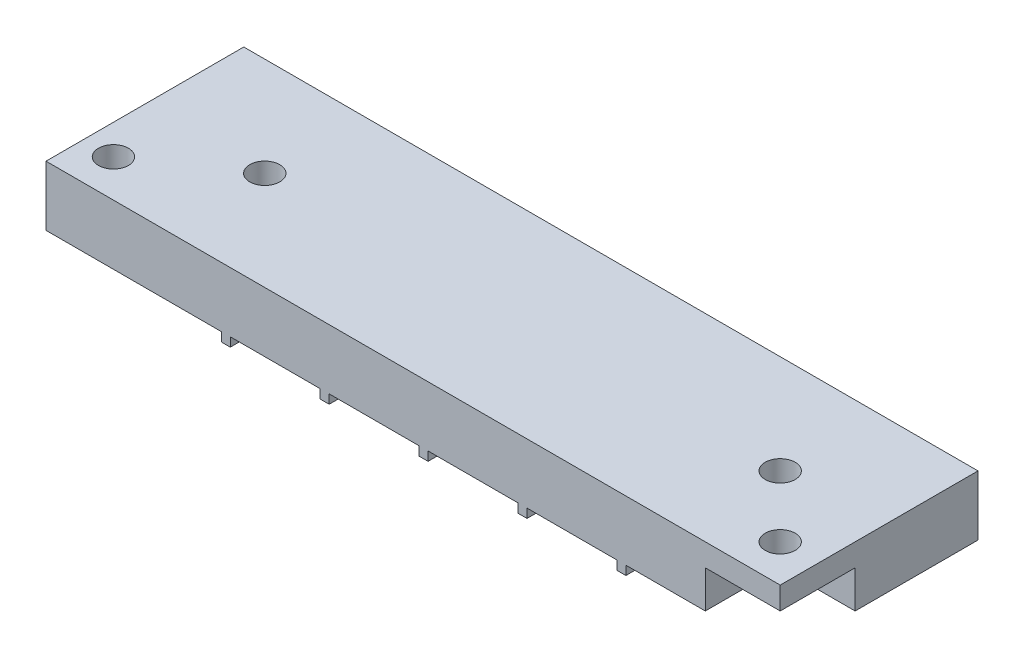
SolidWorks part; units mm, degrees
ref_plane "정면" through (0, 0, 0) normal (0, 0, 1) x (1, 0, 0)
ref_plane "윗면" through (0, 0, 0) normal (0, 1, 0) x (1, 0, 0)
ref_plane "우측면" through (0, 0, 0) normal (1, 0, 0) x (0, 0, -1)
sketch "스케치1" plane through (0, 0, 0) normal (0, 0, 1) x (1, 0, 0)
  line L0 (0, 8.45) -> (110, 8.45)
  line L1 (110, 8.45) -> (110, -8.45)
  line L2 (110, -8.45) -> (0, -8.45)
  line L4 (110, 8.45) -> (30, 8.45) construction
  line L5 (110, 8.45) -> (110, -8.45) construction
  line L6 (110, -8.45) -> (30, -8.45) construction
  line L7 (30, 8.45) -> (30, -8.45) construction
  arc A0 (0, 8.45) -> (0, -8.45) centre (0, 0) ccw
  circle A1 centre (0, 0) radius 5.95 construction
  circle A2 centre (-5.95, 0) radius 1.25
  circle A3 centre (0, 5.95) radius 1.25
  circle A4 centre (5.95, 0) radius 1.25
  circle A5 centre (0, -5.95) radius 1.25
  dimension "D1" = 16.9
  dimension "D4" = 2.5
  dimension "D5" = 2.5
  dimension "D2" = 80
  dimension "D3" = 30
extrude "보스-돌출1" add sketch "스케치1" along normal blind 2.5
sketch "스케치2" plane through (0, 0, 0) normal (0, 0, -1) x (-1, 0, 0)
  line L2 (-110, -8.45) -> (-28, -8.45)
  line L3 (-110, -8.45) -> (-110, -1.45)
  line L4 (-110, -1.45) -> (-28, -1.45)
  line L7 (-28, -8.45) -> (-28, -1.45)
  dimension "D1" = 7
  dimension "D2" = 82
extrude "컷-돌출1" cut sketch "스케치2" against normal blind 2.5
sketch "스케치3" plane through (0, 0, 0) normal (0, 0, -1) x (-1, 0, 0)
  line L1 (-107, 2.55) -> (-28, 2.55)
  line L2 (-107, 2.55) -> (-107, -1.45)
  line L3 (-107, -1.45) -> (-28, -1.45)
  line L4 (-28, 2.55) -> (-28, -1.45)
  dimension "D1" = 4
extrude "보스-돌출2" add sketch "스케치3" along normal blind 10.7
sketch "스케치4" plane through (0, -1.45, 0) normal (0, -1, 0) x (1, 0, 0)
  line L0 (28, -10.7) -> (107, -10.7) construction
  line L1 (67.5, -10.7) -> (67.5, 2.5) construction
  line L2 (28, 2.5) -> (110, 2.5) construction
  line L3 (73.8, -10.7) -> (74.4, -10.7)
  line L4 (67.2, -10.7) -> (67.8, -10.7)
  line L5 (67.2, -10.7) -> (67.2, 2.5)
  line L6 (67.2, 2.5) -> (67.8, 2.5)
  line L7 (67.8, -10.7) -> (67.8, 2.5)
  line L8 (67.2, -10.7) -> (67.8, 2.5) construction
  line L9 (67.2, 2.5) -> (67.8, -10.7) construction
  line L10 (73.8, -10.7) -> (73.8, 2.5)
  line L11 (73.8, 2.5) -> (74.4, 2.5)
  line L12 (74.4, -10.7) -> (74.4, 2.5)
  line L13 (34.6, -10.7) -> (113.6, -10.7) construction
  line L14 (74.1, -10.7) -> (74.1, 2.5) construction
  line L15 (73.8, -10.7) -> (74.4, 2.5) construction
  line L16 (73.8, 2.5) -> (74.4, -10.7) construction
  line L17 (80.4, -10.7) -> (81, -10.7)
  line L18 (80.4, -10.7) -> (80.4, 2.5)
  line L19 (80.4, 2.5) -> (81, 2.5)
  line L20 (81, -10.7) -> (81, 2.5)
  line L21 (41.2, -10.7) -> (120.2, -10.7) construction
  line L22 (80.7, -10.7) -> (80.7, 2.5) construction
  line L23 (80.4, -10.7) -> (81, 2.5) construction
  line L24 (80.4, 2.5) -> (81, -10.7) construction
  line L25 (87, -10.7) -> (87.6, -10.7)
  line L26 (87, -10.7) -> (87, 2.5)
  line L27 (87, 2.5) -> (87.6, 2.5)
  line L28 (87.6, -10.7) -> (87.6, 2.5)
  line L29 (47.8, -10.7) -> (126.8, -10.7) construction
  line L30 (87.3, -10.7) -> (87.3, 2.5) construction
  line L31 (87, -10.7) -> (87.6, 2.5) construction
  line L32 (87, 2.5) -> (87.6, -10.7) construction
  line L33 (93.6, -10.7) -> (94.2, -10.7)
  line L34 (93.6, -10.7) -> (93.6, 2.5)
  line L35 (93.6, 2.5) -> (94.2, 2.5)
  line L36 (94.2, -10.7) -> (94.2, 2.5)
  line L37 (54.4, -10.7) -> (133.4, -10.7) construction
  line L38 (93.9, -10.7) -> (93.9, 2.5) construction
  line L39 (93.6, -10.7) -> (94.2, 2.5) construction
  line L40 (93.6, 2.5) -> (94.2, -10.7) construction
  point P8 (67.5, -4.1)
  point P19 (74.1, -4.1)
  point P28 (80.7, -4.1)
  point P37 (87.3, -4.1)
  point P44 (93.9, -4.1)
  dimension "D1" = 5
extrude "보스-돌출3" add sketch "스케치4" along normal blind 0.6
sketch "스케치5" plane through (0, -1.45, 0) normal (0, -1, 0) x (1, 0, 0)
  line L0 (70.8, 2.5) -> (70.8, -10.7) construction
  line L1 (67.8, 2.5) -> (73.8, 2.5) construction
  line L2 (73.8, -10.7) -> (67.8, -10.7) construction
  line L3 (70.8, -8.95) -> (70.8, 0.75) construction
  line L4 (67.8, -10.7) -> (67.8, 2.5) construction
  line L5 (67.8, 0.75) -> (73.8, 0.75)
  line L6 (67.8, 0.75) -> (67.8, 1.15)
  line L7 (67.8, 1.15) -> (73.8, 1.15)
  line L8 (73.8, 0.75) -> (73.8, 1.15)
  line L9 (73.8, 2.5) -> (73.8, -10.7) construction
  line L10 (70.8, -4.1) -> (73.8, -4.1) construction
  line L11 (73.8, -8.95) -> (73.8, -9.35)
  line L12 (67.8, -9.35) -> (73.8, -9.35)
  line L13 (67.8, -8.95) -> (67.8, -9.35)
  line L14 (67.8, -8.95) -> (73.8, -8.95)
  line L15 (74.4, 0.75) -> (80.4, 0.75)
  line L16 (74.4, 0.75) -> (74.4, 1.15)
  line L17 (74.4, 1.15) -> (80.4, 1.15)
  line L18 (80.4, 0.75) -> (80.4, 1.15)
  line L19 (80.4, -8.95) -> (80.4, -9.35)
  line L20 (74.4, -9.35) -> (80.4, -9.35)
  line L21 (74.4, -8.95) -> (74.4, -9.35)
  line L22 (74.4, -8.95) -> (80.4, -8.95)
  line L23 (77.4, 2.5) -> (77.4, -10.7) construction
  line L24 (77.4, -8.95) -> (77.4, 0.75) construction
  line L25 (77.4, -4.1) -> (80.4, -4.1) construction
  line L26 (81, 0.75) -> (87, 0.75)
  line L27 (81, 0.75) -> (81, 1.15)
  line L28 (81, 1.15) -> (87, 1.15)
  line L29 (87, 0.75) -> (87, 1.15)
  line L30 (87, -8.95) -> (87, -9.35)
  line L31 (81, -9.35) -> (87, -9.35)
  line L32 (81, -8.95) -> (81, -9.35)
  line L33 (81, -8.95) -> (87, -8.95)
  line L34 (84, 2.5) -> (84, -10.7) construction
  line L35 (84, -8.95) -> (84, 0.75) construction
  line L36 (84, -4.1) -> (87, -4.1) construction
  line L37 (87.6, 0.75) -> (93.6, 0.75)
  line L38 (87.6, 0.75) -> (87.6, 1.15)
  line L39 (87.6, 1.15) -> (93.6, 1.15)
  line L40 (93.6, 0.75) -> (93.6, 1.15)
  line L41 (93.6, -8.95) -> (93.6, -9.35)
  line L42 (87.6, -9.35) -> (93.6, -9.35)
  line L43 (87.6, -8.95) -> (87.6, -9.35)
  line L44 (87.6, -8.95) -> (93.6, -8.95)
  line L45 (90.6, 2.5) -> (90.6, -10.7) construction
  line L46 (90.6, -8.95) -> (90.6, 0.75) construction
  line L47 (90.6, -4.1) -> (93.6, -4.1) construction
  dimension "D1" = 4
extrude "보스-돌출4" add sketch "스케치5" along normal blind 0.4
sketch "스케치11" plane through (0, -1.45, 0) normal (0, -1, 0) x (1, 0, 0)
  line L0 (107, 0) -> (107, 2.5) construction
  line L1 (94.2, 2.5) -> (110, 2.5) construction
  line L2 (107, 0) -> (102, 0) construction
  line L3 (28, 0) -> (33, 0) construction
  circle A0 centre (102, 0) radius 1
  circle A1 centre (33, 0) radius 1
extrude "컷-돌출5" cut sketch "스케치11" against normal blind 5
sketch "스케치12" plane through (0, 2.55, 0) normal (0, 1, 0) x (1, 0, 0)
  line L0 (34, 0) -> (101, 0) construction
  line L2 (63.5, 0) -> (63.5, 6.6879)
  line L3 (63.5, 6.6879) -> (71.5, 6.6879)
  line L4 (71.5, 0) -> (71.5, 6.6879)
  line L5 (67.5, 0) -> (71.5, 6.6879) construction
  line L6 (63.5, 6.6879) -> (67.5, 0) construction
  line L7 (63.5, 0) -> (71.5, 0)
  point P0 (67.5, 0)
extrude "보스-돌출6" add sketch "스케치12" along normal blind 5.9
sketch "스케치13" plane through (0, 0, -6.6879) normal (0, 0, -1) x (-1, 0, 0)
  line L0 (-67.5, 2.55) -> (-67.5, 4.55) construction
  line L1 (-71.5, 2.55) -> (-63.5, 2.55) construction
  circle A0 centre (-67.5, 4.55) radius 1
extrude "컷-돌출6" cut sketch "스케치13" against normal blind 8 contours A0
sketch "스케치15" plane through (0, 0, 2.5) normal (0, 0, 1) x (1, 0, 0)
  line L1 (67.5, 2.55) -> (63.5, 2.55) construction
  line L2 (67.5, 8.45) -> (71.5, 8.45) construction
  line L3 (110, 8.45) -> (0, 8.45) construction
  line L5 (63.5, 2.55) -> (71.5, 2.55)
  line L6 (63.5, 2.55) -> (63.5, 8.45)
  line L7 (63.5, 8.45) -> (71.5, 8.45)
  line L8 (71.5, 2.55) -> (71.5, 8.45)
extrude "컷-돌출11" cut sketch "스케치15" against normal blind 5
sketch "스케치16" plane through (0, 0, 0) normal (0, 0, -1) x (-1, 0, 0)
  line L0 (-28, -8.45) -> (0, -8.45)
  line L1 (0, 8.45) -> (-63.5, 8.45)
  line L2 (-63.5, 8.45) -> (-63.5, 2.55)
  line L3 (-63.5, 2.55) -> (-28, 2.55)
  line L4 (-28, 2.55) -> (-28, -8.45)
  line L5 (-71.5, 2.55) -> (-71.5, 8.45)
  line L6 (-71.5, 8.45) -> (-110, 8.45)
  line L7 (-110, 8.45) -> (-110, -1.45)
  line L8 (-110, -1.45) -> (-107, -1.45)
  line L9 (-107, -1.45) -> (-107, 2.55)
  line L10 (-107, 2.55) -> (-71.5, 2.55)
  arc A0 (0, -8.45) -> (0, 8.45) centre (0, 0) ccw
  arc A1 (0, -8.45) -> (0, 8.45) centre (0, 0) ccw construction
extrude "컷-돌출12" cut sketch "스케치16" against normal blind 5
sketch "스케치17" plane through (63.5, 0, 0) normal (-1, 0, 0) x (0, 0, 1)
  line L1 (-6.6879, 2.55) -> (-2.5, 2.55)
  line L2 (-6.6879, 2.55) -> (-6.6879, 8.45)
  line L3 (-6.6879, 8.45) -> (-2.5, 8.45)
  line L4 (-2.5, 2.55) -> (-2.5, 8.45)
extrude "컷-돌출13" cut sketch "스케치17" against normal blind 15
sketch "스케치18" plane through (28, 0, 0) normal (-1, 0, 0) x (0, 0, 1)
  line L1 (2.5, 2.55) -> (-10.7, 2.55)
  line L2 (2.5, 2.55) -> (2.5, -1.45)
  line L3 (2.5, -1.45) -> (-10.7, -1.45)
  line L4 (-10.7, 2.55) -> (-10.7, -1.45)
extrude "컷-돌출14" cut sketch "스케치18" against normal blind 2.5
sketch "스케치19" plane through (107, 0, 0) normal (1, 0, 0) x (0, 0, -1)
  line L1 (-2.5, -1.45) -> (10.7, -1.45)
  line L2 (-2.5, -1.45) -> (-2.5, 2.55)
  line L3 (-2.5, 2.55) -> (10.7, 2.55)
  line L4 (10.7, -1.45) -> (10.7, 2.55)
extrude "컷-돌출15" cut sketch "스케치19" against normal blind 2.5
sketch "스케치21" plane through (0, -2.05, 0) normal (0, -1, 0) x (1, 0, 0)
  line L0 (80.4, -4.1) -> (81, -4.1) construction
  line L1 (80.4, 2.5) -> (80.4, -10.7) construction
  line L2 (81, -10.7) -> (81, 2.5) construction
  line L3 (80.7, -4.1) -> (63.5, -4.1) construction
  line L4 (80.7, -4.1) -> (80.7, -10.7) construction
  line L5 (80.4, -10.7) -> (81, -10.7) construction
  circle A0 centre (63.5, -4.1) radius 1
  circle A1 centre (97.9, -4.1) radius 1
extrude "컷-돌출16" cut sketch "스케치21" against normal blind 10 contours A0 | A1
sketch "스케치22" plane through (0, -1.45, 0) normal (0, -1, 0) x (1, 0, 0)
  line L1 (104.5, 2.5) -> (99.5, 2.5)
  line L2 (104.5, 2.5) -> (104.5, -2.5)
  line L3 (104.5, -2.5) -> (99.5, -2.5)
  line L4 (99.5, 2.5) -> (99.5, -2.5)
extrude "컷-돌출17" cut sketch "스케치22" against normal blind 2.5
sketch "스케치23" plane through (30.5, 0, 0) normal (-1, 0, 0) x (0, 0, 1)
  line L1 (2.5, 2.55) -> (-10.7, 2.55)
  line L2 (2.5, 2.55) -> (2.5, -1.45)
  line L3 (2.5, -1.45) -> (-10.7, -1.45)
  line L4 (-10.7, 2.55) -> (-10.7, -1.45)
extrude "컷-돌출18" cut sketch "스케치23" against normal blind 25
sketch "스케치24" plane through (0, -1.45, 0) normal (0, -1, 0) x (1, 0, 0)
  line L0 (55.5, 2.5) -> (67.2, 2.5) construction
  line L1 (55.5, -10.7) -> (55.5, 2.5) construction
  circle A0 centre (57.5, 0) radius 1
  dimension "D1" = 2.5
  dimension "D2" = 2
extrude "컷-돌출19" cut sketch "스케치24" against normal blind 25
